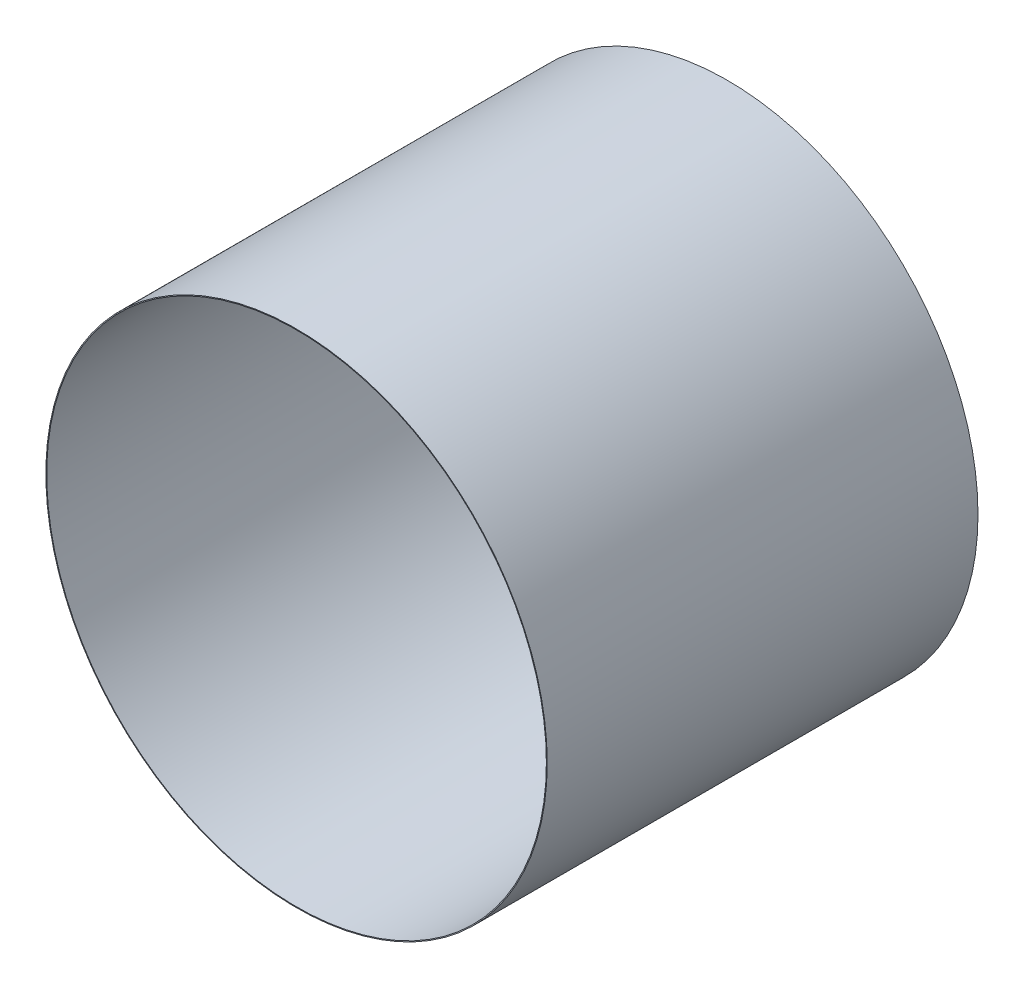
SolidWorks part; units mm, degrees
ref_plane "Front Plane" through (0, 0, 0) normal (0, 0, 1) x (1, 0, 0)
ref_plane "Top Plane" through (0, 0, 0) normal (0, 1, 0) x (1, 0, 0)
ref_plane "Right Plane" through (0, 0, 0) normal (1, 0, 0) x (0, 0, -1)
sketch "Sketch1" plane through (0, 0, 0) normal (0, 0, 1) x (1, 0, 0)
  circle A0 centre (0, 0) radius 14.55
  circle A1 centre (0, 0) radius 14.5
  dimension "D1" = 29
  dimension "D2" = 29.1
extrude "Boss-Extrude1" add sketch "Sketch1" along normal blind 25
